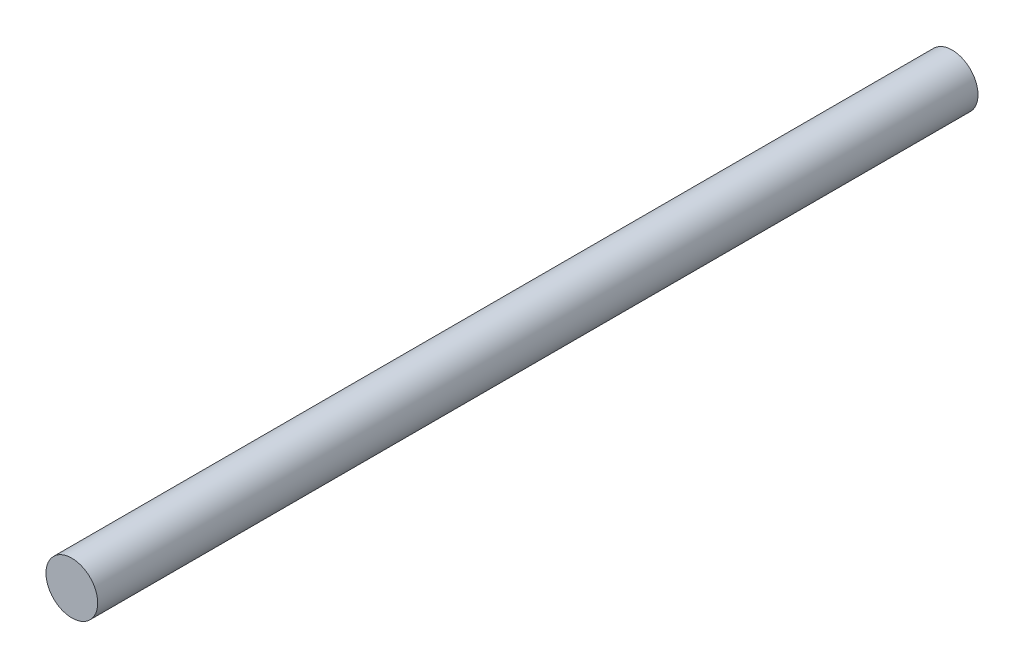
SolidWorks part; units mm, degrees
ref_plane "前视基准面" through (0, 0, 0) normal (0, 0, 1) x (1, 0, 0)
ref_plane "上视基准面" through (0, 0, 0) normal (0, 1, 0) x (1, 0, 0)
ref_plane "右视基准面" through (0, 0, 0) normal (1, 0, 0) x (0, 0, -1)
sketch "草图1" plane through (0, 0, 0) normal (0, 0, 1) x (1, 0, 0)
  circle A0 centre (0, 0) radius 2.5
  dimension "D1" = 5
extrude "凸台-拉伸1" add sketch "草图1" along normal blind 85
cosmetic thread "装饰螺纹线1" parameters "D1"=16, "D2"=4
